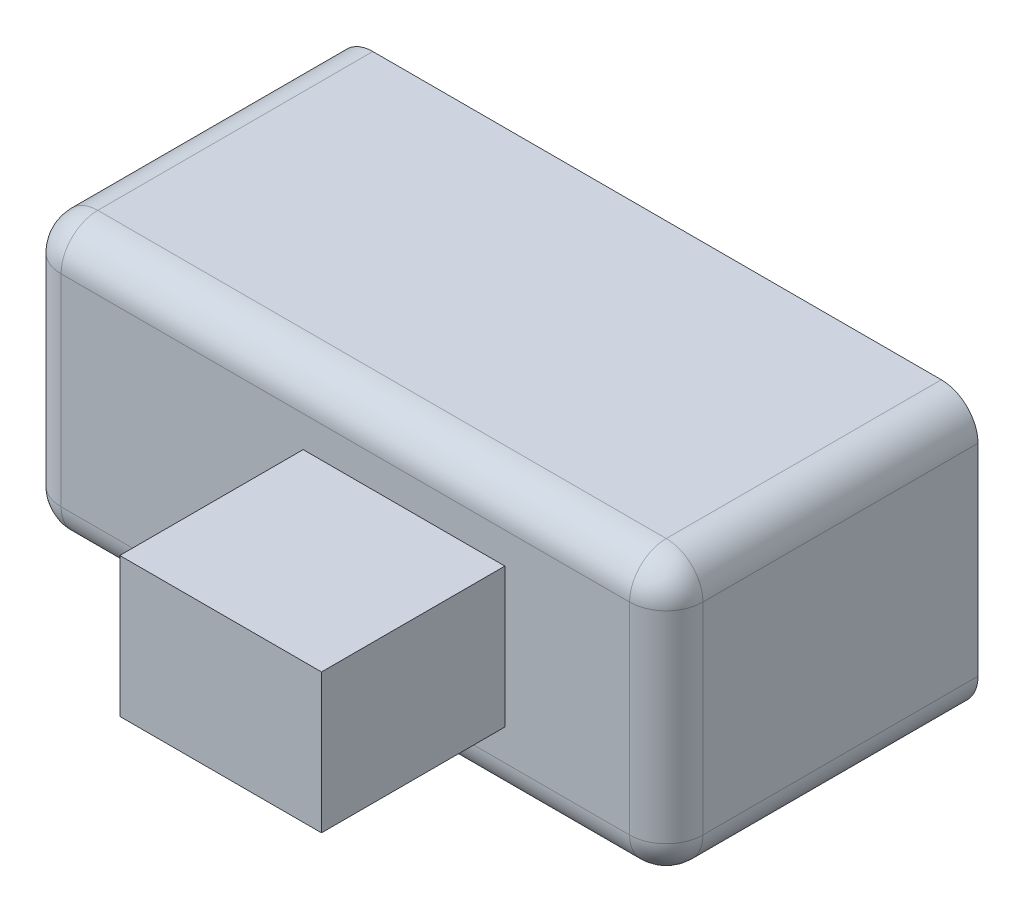
SolidWorks part; units mm, degrees
ref_plane "Front Plane" through (0, 0, 0) normal (0, 0, 1) x (1, 0, 0)
ref_plane "Top Plane" through (0, 0, 0) normal (0, 1, 0) x (1, 0, 0)
ref_plane "Right Plane" through (0, 0, 0) normal (1, 0, 0) x (0, 0, -1)
sketch "Sketch1" plane through (0, 0, 0) normal (0, 0, 1) x (1, 0, 0)
  line L1 (-8.75, 3.75) -> (8.75, 3.75)
  line L2 (-8.75, 3.75) -> (-8.75, -3.75)
  line L3 (-8.75, -3.75) -> (8.75, -3.75)
  line L4 (8.75, 3.75) -> (8.75, -3.75)
  line L5 (-8.75, 3.75) -> (8.75, -3.75) construction
  line L6 (-8.75, -3.75) -> (8.75, 3.75) construction
  point P0 (0, 0)
  dimension "D1" = 7.5
  dimension "D2" = 17.5
extrude "Boss-Extrude1" add sketch "Sketch1" along normal blind 8.5
sketch "Sketch2" plane through (0, 0, 8.5) normal (0, 0, 1) x (1, 0, 0)
  line L0 (0, 0) -> (1.6, 0) construction
  line L1 (-1.15, 1.9) -> (4.35, 1.9)
  line L2 (-1.15, 1.9) -> (-1.15, -1.9)
  line L3 (-1.15, -1.9) -> (4.35, -1.9)
  line L4 (4.35, 1.9) -> (4.35, -1.9)
  line L5 (-1.15, 1.9) -> (4.35, -1.9) construction
  line L6 (-1.15, -1.9) -> (4.35, 1.9) construction
  point P0 (1.6, 0)
  dimension "D1" = 3.8
  dimension "D2" = 5.5
  dimension "D3" = 1.6
extrude "Boss-Extrude2" add sketch "Sketch2" along normal blind 5
fillet "Fillet1" radius 1 4 edges at (8.75, -3.75, 4.25) (8.75, 3.75, 4.25) (-8.75, -3.75, 4.25) (-8.75, 3.75, 4.25)
fillet "Fillet2" radius 1 8 edges at (8.4571, -3.4571, 8.5) (0, -3.75, 8.5) (-8.4571, -3.4571, 8.5) (-8.75, 0, 8.5) (-8.4571, 3.4571, 8.5) (0, 3.75, 8.5) (8.4571, 3.4571, 8.5) (8.75, 0, 8.5)
